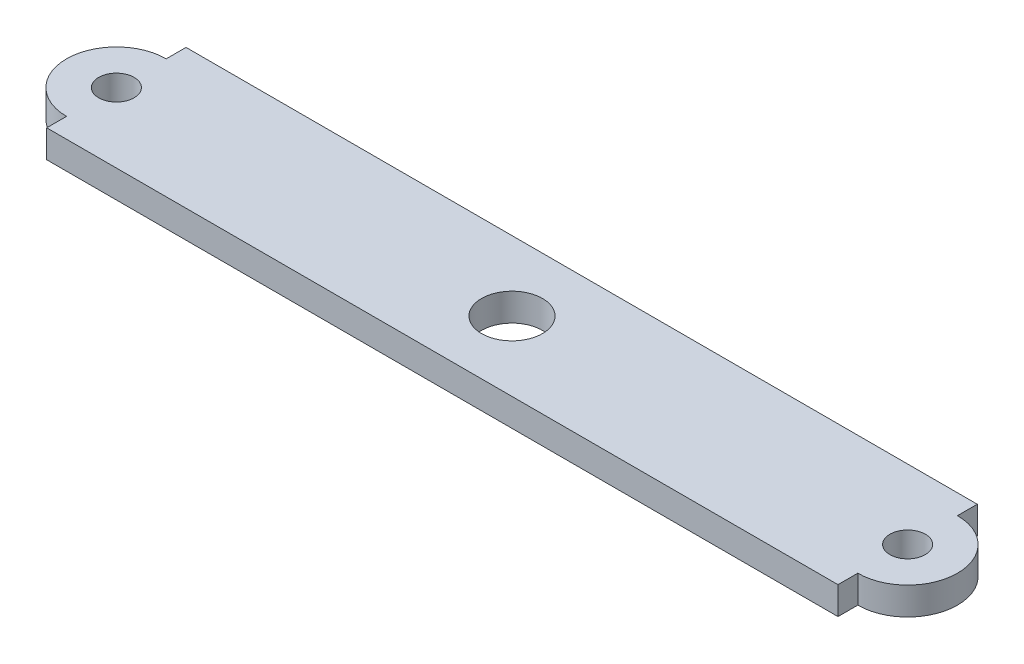
SolidWorks part; units mm, degrees
ref_plane "Front Plane" through (0, 0, 0) normal (0, 0, 1) x (1, 0, 0)
ref_plane "Top Plane" through (0, 0, 0) normal (0, 1, 0) x (1, 0, 0)
ref_plane "Right Plane" through (0, 0, 0) normal (1, 0, 0) x (0, 0, -1)
sketch "Sketch1" plane through (0, 0, 0) normal (0, 1, 0) x (1, 0, 0)
  line L1 (35.7128, -6.2872) -> (-35.7128, -6.2872)
  line L2 (35.7128, -6.2872) -> (35.7128, 6.2872)
  line L3 (35.7128, 6.2872) -> (-35.7128, 6.2872)
  line L4 (-35.7128, -6.2872) -> (-35.7128, 6.2872)
  line L5 (35.7128, -6.2872) -> (-35.7128, 6.2872) construction
  line L6 (35.7128, 6.2872) -> (-35.7128, -6.2872) construction
  circle A0 centre (35.7128, 0) radius 6.2872 construction
  circle A1 centre (-35.7128, 0) radius 6.2872 construction
  circle A2 centre (35.7128, 0) radius 11.2872
  circle A3 centre (-35.7128, 0) radius 11.2872
  circle A4 centre (0, 0) radius 2.75
  circle A5 centre (-35.7128, 0) radius 1.6
  circle A6 centre (35.7128, 0) radius 1.6
  circle A7 centre (-35.7128, 0) radius 4.5
  circle A8 centre (35.7128, 0) radius 4.5
  point P0 (0, 0)
  dimension "D3" = 5.5
  dimension "D4" = 3.2
  dimension "D5" = 9
  dimension "D1" = 84
  dimension "D2" = 5
extrude "Boss-Extrude1" add sketch "Sketch1" along normal blind 2.5 contours A3 L1 A2 L3 A4 | L1 A3 L3 A1 | L4 A1 | L4 A1 | L3 A2 L1 A0 | L2 A0 | L2 A0
equation "\"cup_diameter\"= 8.5cm"
equation "\"cup_wall_thickness\"= 0.2cm"
equation "\"wave_generator_interference\"= 0.1cm"
equation "\"D1@Sketch1\"=\"cup_diameter\"-\"cup_wall_thickness\"+\"wave_generator_interference\""
equation "\"motor_shaft_diamter\"= 0.5"
equation "\"D3@Sketch1\"=\"motor_shaft_diamter\" + 0.05"
